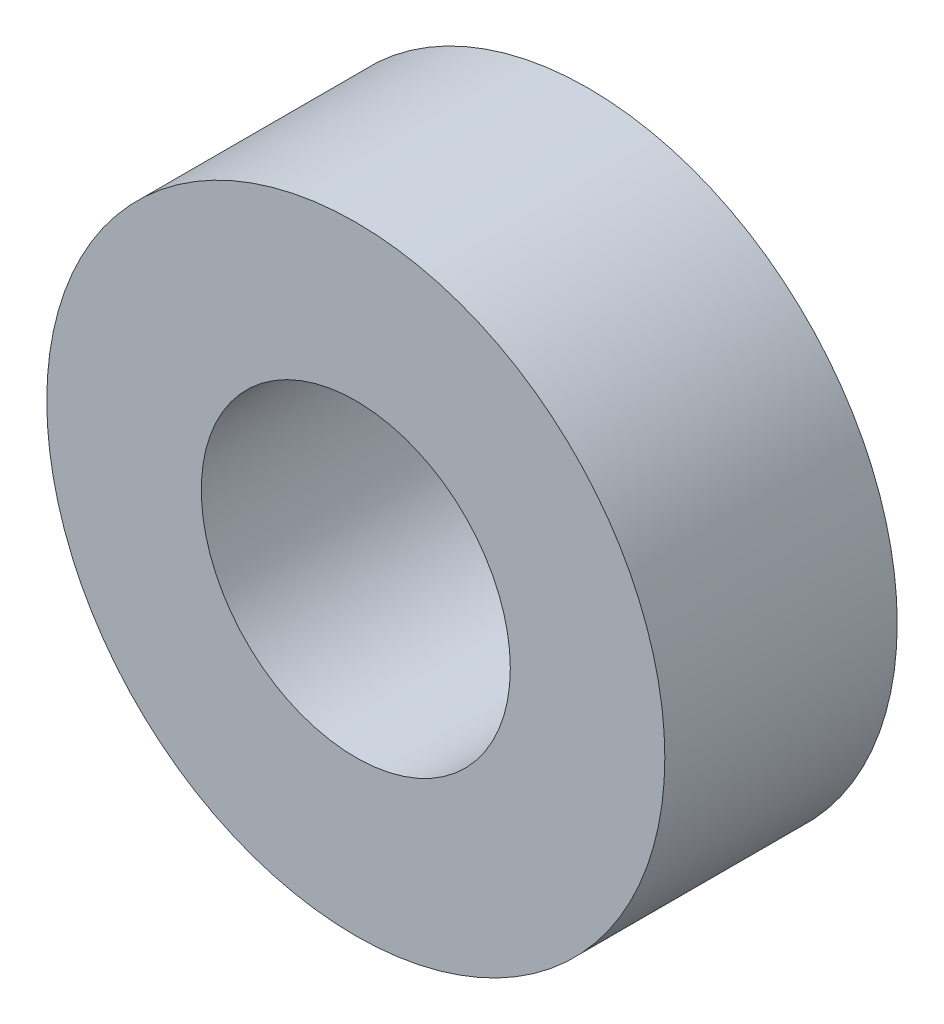
SolidWorks part; units mm, degrees
ref_plane "Front Plane" through (0, 0, 0) normal (0, 0, 1) x (1, 0, 0)
ref_plane "Top Plane" through (0, 0, 0) normal (0, 1, 0) x (1, 0, 0)
ref_plane "Right Plane" through (0, 0, 0) normal (1, 0, 0) x (0, 0, -1)
sketch "Sketch1" plane through (0, 0, 0) normal (0, 0, 1) x (1, 0, 0)
  circle A0 centre (0, 0) radius 6.35
  circle A1 centre (0, 0) radius 3.175
  dimension "D1" = 6.35
  dimension "D2" = 12.7
extrude "Boss-Extrude1" add sketch "Sketch1" along normal blind 4.7752
